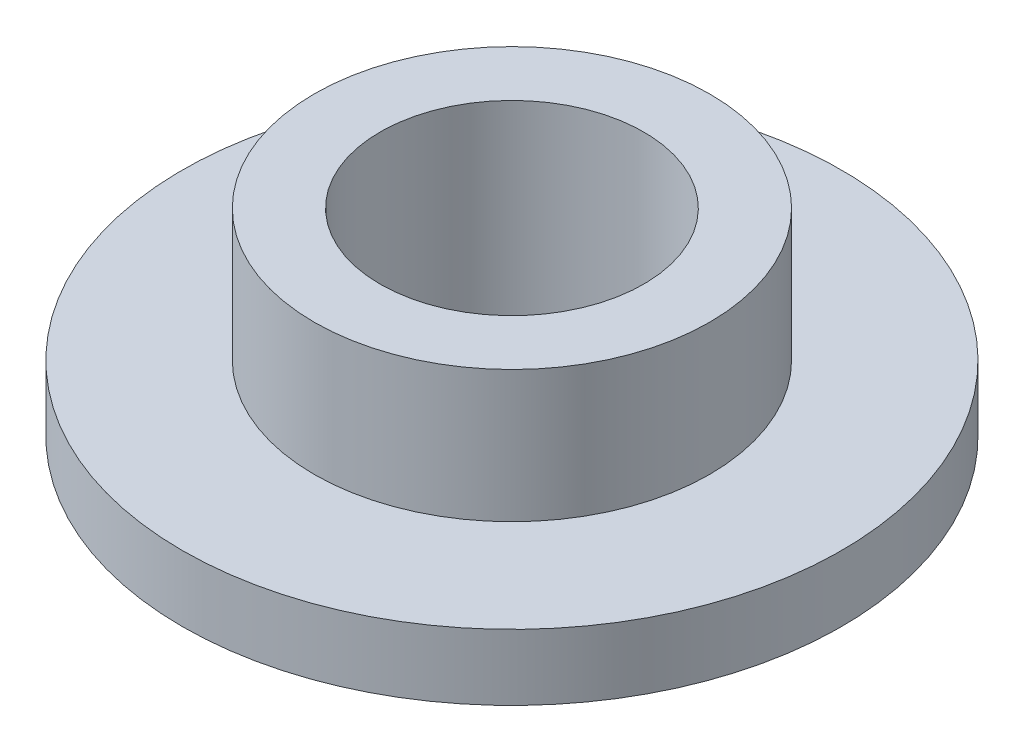
SolidWorks part; units mm, degrees
ref_plane "Front Plane" through (0, 0, 0) normal (0, 0, 1) x (1, 0, 0)
ref_plane "Top Plane" through (0, 0, 0) normal (0, 1, 0) x (1, 0, 0)
ref_plane "Right Plane" through (0, 0, 0) normal (1, 0, 0) x (0, 0, -1)
sketch "Sketch1" plane through (0, 0, 0) normal (0, 1, 0) x (1, 0, 0)
  circle A0 centre (0, 0) radius 5
  circle A1 centre (0, 0) radius 2
extrude "Boss-Extrude3" add sketch "Sketch1" along normal blind 1
sketch "Sketch3" plane through (0, 1, 0) normal (0, 1, 0) x (1, 0, 0)
  circle A0 centre (0, 0) radius 3
  circle A1 centre (0, 0) radius 2
extrude "Boss-Extrude4" add sketch "Sketch3" along normal blind 2
